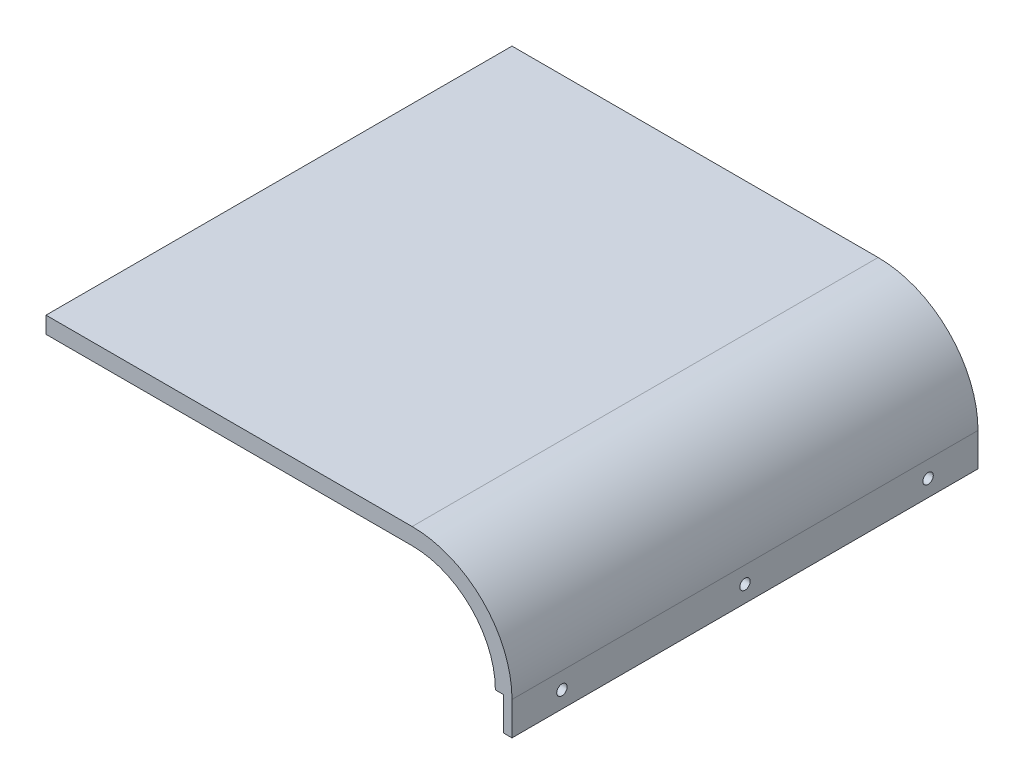
SolidWorks part; units mm, degrees
ref_plane "Front Plane" through (0, 0, 0) normal (0, 0, 1) x (1, 0, 0)
ref_plane "Top Plane" through (0, 0, 0) normal (0, 1, 0) x (1, 0, 0)
ref_plane "Right Plane" through (0, 0, 0) normal (1, 0, 0) x (0, 0, -1)
sketch "Sketch1" plane through (0, 0, 0) normal (0, 0, 1) x (1, 0, 0)
  line L0 (-139.7, 0) -> (139.7, 0)
  line L1 (139.7, 0) -> (139.7, -152.4) construction
  line L2 (139.7, -76.2) -> (215.9, -76.2) construction
  line L3 (-139.7, -12.7) -> (139.7, -12.7)
  line L4 (-139.7, 0) -> (-139.7, -12.7)
  line L5 (215.9, -76.2) -> (203.2, -76.2)
  circle A0 centre (139.7, -76.2) radius 76.2 construction
  arc A1 (139.7, 0) -> (215.9, -76.2) centre (139.7, -76.2) cw
  arc A2 (139.7, -12.7) -> (203.2, -76.2) centre (139.7, -76.2) cw
  point P4 (0, 0)
  dimension "D1" = 152.4
  dimension "D2" = 355.6
  dimension "D3" = 12.7
extrude "Boss-Extrude1" add sketch "Sketch1" along normal blind 177.8 and the other way blind 177.8
sketch "Sketch2" plane through (0, -76.2, 0) normal (0, -1, 0) x (1, 0, 0)
  line L0 (203.2, 177.8) -> (215.9, 177.8) construction
  line L1 (209.55, 177.8) -> (215.9, 177.8)
  line L2 (209.55, 177.8) -> (209.55, -177.8)
  line L3 (209.55, -177.8) -> (215.9, -177.8)
  line L4 (215.9, 177.8) -> (215.9, -177.8)
extrude "Boss-Extrude2" add sketch "Sketch2" along normal blind 25.4
sketch "Sketch3" plane through (215.9, 0, 0) normal (1, 0, 0) x (0, 0, -1)
  line L0 (-177.8, -88.9) -> (177.8, -88.9) construction
  line L1 (-177.8, -101.6) -> (-177.8, -76.2) construction
  line L2 (177.8, -101.6) -> (177.8, -76.2) construction
  line L3 (0, -76.2) -> (0, -101.6) construction
  line L4 (177.8, -76.2) -> (-177.8, -76.2) construction
  line L5 (177.8, -101.6) -> (-177.8, -101.6) construction
  line L6 (139.7, -76.2) -> (139.7, -101.6) construction
  line L7 (-139.7, -76.2) -> (-139.7, -101.6) construction
  circle A0 centre (-139.7, -88.9) radius 3.9687
  circle A1 centre (0, -88.9) radius 3.9687
  circle A2 centre (139.7, -88.9) radius 3.9687
  dimension "D3" = 7.9375
  dimension "D1" = 139.7
  dimension "D2" = 139.7
extrude "Cut-Extrude1" cut sketch "Sketch3" against normal blind 25.4
